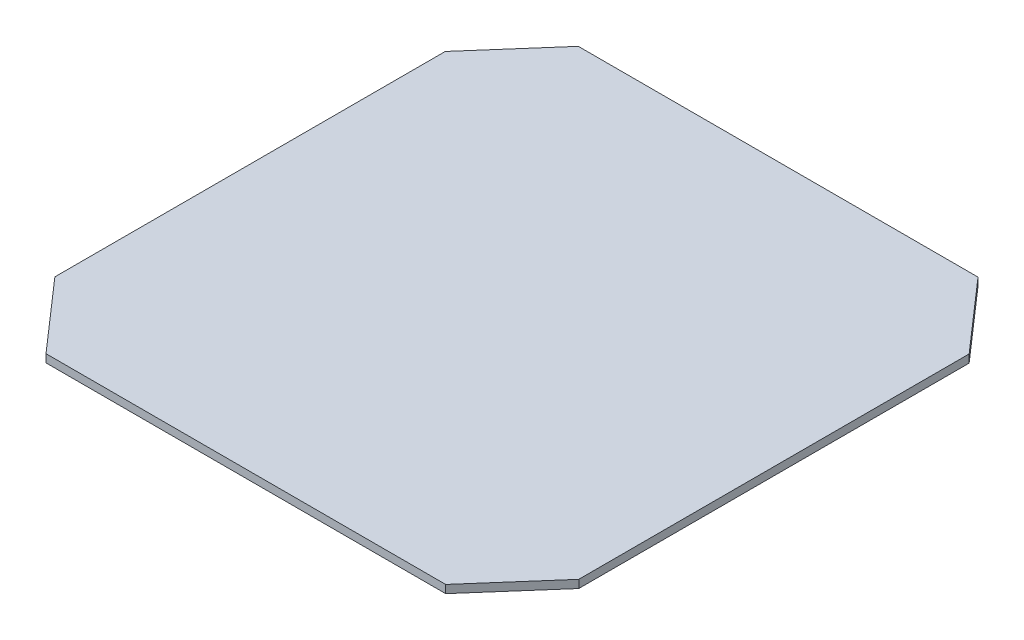
SolidWorks part; units mm, degrees
ref_plane "Plan de face" through (0, 0, 0) normal (0, 0, 1) x (1, 0, 0)
ref_plane "Plan de dessus" through (0, 0, 0) normal (0, 1, 0) x (1, 0, 0)
ref_plane "Plan de droite" through (0, 0, 0) normal (1, 0, 0) x (0, 0, -1)
sketch "Esquisse1" plane through (0, 0, 0) normal (0, 1, 0) x (1, 0, 0)
  line L0 (-125, 166.4835) -> (125, 166.4835)
  line L1 (-125, -166.4835) -> (125, -166.4835)
  line L2 (-163.8462, 122.0879) -> (-163.8462, -122.0879)
  line L3 (-163.8462, 122.0879) -> (-125, 166.4835)
  line L4 (-163.8462, -122.0879) -> (-125, -166.4835)
  line L5 (163.8462, -122.0879) -> (125, -166.4835)
  line L6 (163.8462, 122.0879) -> (163.8462, -122.0879)
  line L7 (163.8462, 122.0879) -> (125, 166.4835)
  point P3 (0, 166.4835)
  point P8 (-163.8462, 0)
extrude "Boss.-Extru.1" add sketch "Esquisse1" along normal blind 5
